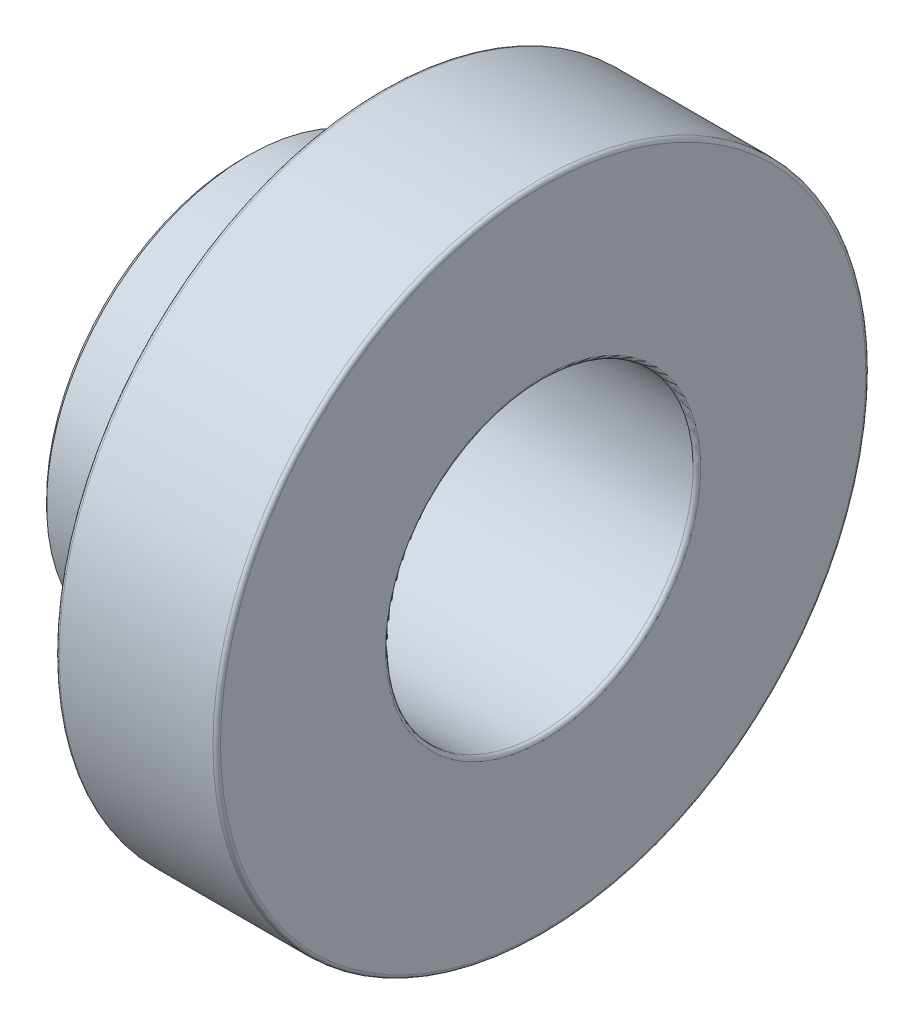
SolidWorks part; units mm, degrees
ref_plane "Front Plane" through (0, 0, 0) normal (0, 0, 1) x (1, 0, 0)
ref_plane "Top Plane" through (0, 0, 0) normal (0, 1, 0) x (1, 0, 0)
ref_plane "Right Plane" through (0, 0, 0) normal (1, 0, 0) x (0, 0, -1)
sketch "Sketch1" plane through (0, 0, 0) normal (0, 0, 1) x (1, 0, 0)
  line L0 (0, 12.95) -> (0, 8)
  line L3 (0, 8) -> (-5.5, 8)
  line L4 (-5.5, 8) -> (-5.5, 6.1)
  line L5 (-5.5, 6.1) -> (6.4, 6.1)
  line L7 (6.4, 6.1) -> (6.4, 12.95)
  line L11 (6.4, 12.95) -> (0, 12.95)
  line L12 (6.4, 0) -> (0, 0) construction
  dimension "D_s" = 12.2
  dimension "D1_s" = 16
  dimension "MSM_4" = 25.9
  dimension "MSM_5" = 11.9
  dimension "A_s" = 5.5
revolve "Revolve1" add sketch "Sketch1" angle 360 about L12
fillet "Fillet1" radius 0.15 2 edges at (0, 12.95, 0) (6.4, 12.95, 0)
fillet "Fillet2" radius 0.15 1 edges at (6.4, 6.1, 0)
chamfer "Chamfer1" distance 0.2 angle 45 2 edges at (-5.5, 6.1, 0) (-5.5, 8, 0)
